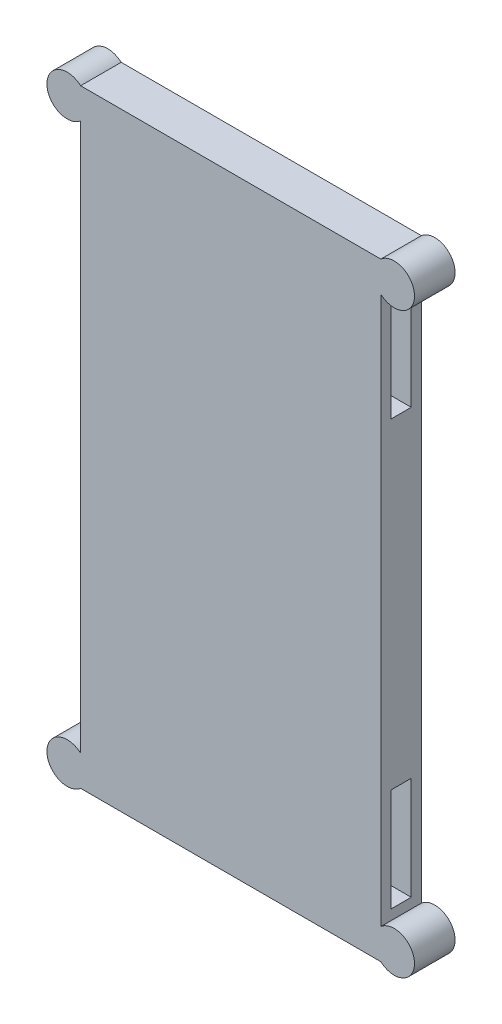
SolidWorks part; units mm, degrees
ref_plane "Front Plane" through (0, 0, 0) normal (0, 0, 1) x (1, 0, 0)
ref_plane "Top Plane" through (0, 0, 0) normal (0, 1, 0) x (1, 0, 0)
ref_plane "Right Plane" through (0, 0, 0) normal (1, 0, 0) x (0, 0, -1)
sketch "Sketch1" plane through (0, 0, 0) normal (0, 0, 1) x (1, 0, 0)
  line L0 (0, 0) -> (148, 0)
  line L1 (148, 0) -> (148, 300)
  line L2 (148, 300) -> (0, 300)
  line L3 (0, 300) -> (0, 0)
  dimension "D1" = 148
  dimension "D2" = 300
extrude "Boss-Extrude1" add sketch "Sketch1" along normal blind 20
sketch "Sketch3" plane through (0, 0, 0) normal (0, 0, -1) x (-1, 0, 0)
  line L0 (0, 0) -> (0, 15)
  line L1 (0, 300) -> (0, 0) construction
  line L2 (-148, 0) -> (-148, 15)
  line L3 (-148, 0) -> (-148, 300) construction
  line L4 (-148, 300) -> (-148, 285)
  line L5 (0, 300) -> (0, 285)
  arc A0 (0, 0) -> (0, 15) centre (6.6144, 7.5) ccw
  arc A1 (-148, 0) -> (-148, 15) centre (-154.6144, 7.5) cw
  arc A2 (-148, 300) -> (-148, 285) centre (-154.6144, 292.5) ccw
  arc A3 (0, 300) -> (0, 285) centre (6.6144, 292.5) cw
  dimension "D2" = 10
  dimension "D4" = 10
  dimension "D6" = 10
  dimension "D8" = 10
  dimension "D1" = 15
  dimension "D3" = 15
  dimension "D5" = 15
  dimension "D7" = 15
extrude "Boss-Extrude2" add sketch "Sketch3" against normal blind 20
sketch "Sketch4" plane through (0, 0, 0) normal (0, 0, -1) x (-1, 0, 0)
  circle A0 centre (6.6144, 7.5) radius 2.5
  circle A1 centre (-154.6144, 7.5) radius 2.5
  circle A2 centre (-154.6144, 292.5) radius 2.5
  circle A3 centre (6.6144, 292.5) radius 2.5
  dimension "D1" = 5
  dimension "D2" = 5
  dimension "D3" = 5
  dimension "D4" = 5
extrude "Cut-Extrude2" cut sketch "Sketch4" against normal blind 10
sketch "Sketch5" plane through (148, 0, 0) normal (1, 0, 0) x (0, 0, -1)
  line L0 (-20, 15) -> (-20, 285) construction
  line L1 (-15, 280) -> (-5, 280)
  line L2 (-15, 280) -> (-15, 229.2)
  line L3 (-15, 229.2) -> (-5, 229.2)
  line L4 (-5, 280) -> (-5, 229.2)
  line L5 (-15, 70.8) -> (-5, 70.8)
  line L6 (-15, 70.8) -> (-15, 20)
  line L7 (-15, 20) -> (-5, 20)
  line L8 (-5, 70.8) -> (-5, 20)
  line L9 (0, 15) -> (0, 285) construction
  line L12 (-20, 285) -> (0, 285) construction
  line L14 (-20, 15) -> (0, 15) construction
  dimension "D1" = 5
  dimension "D2" = 5
  dimension "D3" = 50.8
  dimension "D4" = 50.8
  dimension "D5" = 5
  dimension "D6" = 5
  dimension "D7" = 5
  dimension "D8" = 5
extrude "Cut-Extrude3" cut sketch "Sketch5" against normal up to next
sketch "Sketch7" plane through (0, 0, 0) normal (0, 0, -1) x (-1, 0, 0)
  line L0 (-74, 0) -> (-74, 300) construction
  line L1 (0, 0) -> (-148, 0) construction
  line L2 (-148, 300) -> (0, 300) construction
  text T0 "Lift Labs" font "Century Gothic" height in points 72
extrude "Cut-Extrude4" cut sketch "Sketch7" against normal blind 5
